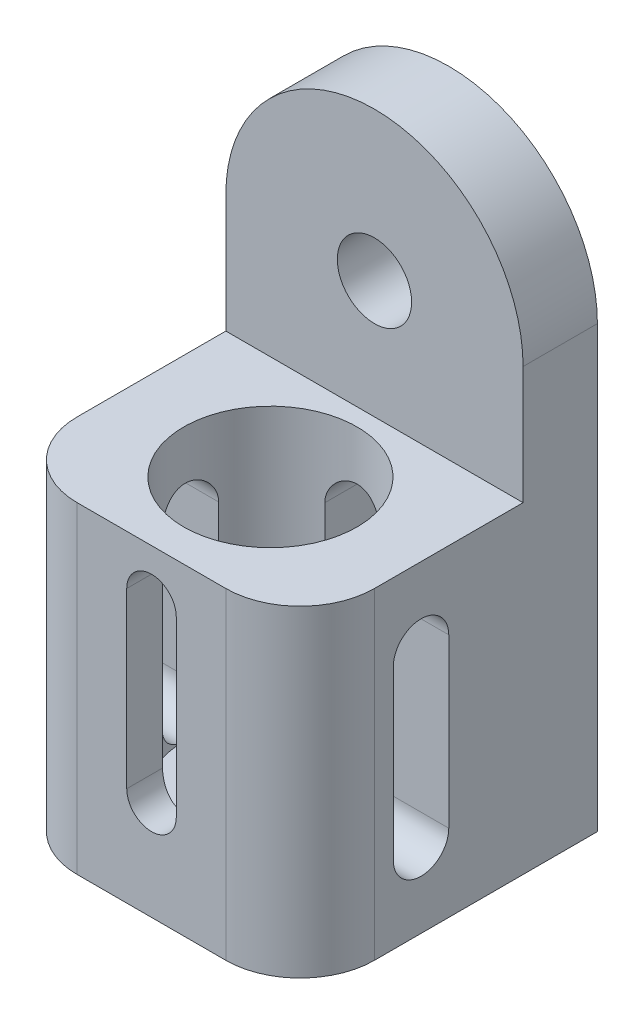
SolidWorks part; units mm, degrees
material "6061-T6 (SS)"
ref_plane "Front Plane" through (0, 0, 0) normal (0, 0, 1) x (1, 0, 0)
ref_plane "Top Plane" through (0, 0, 0) normal (0, 1, 0) x (1, 0, 0)
ref_plane "Right Plane" through (0, 0, 0) normal (1, 0, 0) x (0, 0, -1)
sketch "Sketch1" plane through (0, 0, 0) normal (0, 1, 0) x (1, 0, 0)
  line L1 (-38.1, -38.1) -> (38.1, -38.1)
  line L2 (-38.1, -38.1) -> (-38.1, 38.1)
  line L3 (-38.1, 38.1) -> (38.1, 38.1)
  line L4 (38.1, -38.1) -> (38.1, 38.1)
  line L5 (-38.1, -38.1) -> (38.1, 38.1) construction
  line L6 (-38.1, 38.1) -> (38.1, -38.1) construction
  point P0 (0, 0)
  dimension "D1" = 76.2
  dimension "D2" = 76.2
extrude "Boss-Extrude1" add sketch "Sketch1" against normal blind 82.55
sketch "Sketch2" plane through (0, 0, 0) normal (0, 1, 0) x (1, 0, 0)
  line L0 (38.1, -38.1) -> (38.1, 38.1) construction
  line L1 (-38.1, 38.1) -> (38.1, 38.1)
  line L2 (-38.1, 38.1) -> (-38.1, 19.05)
  line L3 (-38.1, 19.05) -> (38.1, 19.05)
  line L4 (38.1, 38.1) -> (38.1, 19.05)
  dimension "D1" = 19.05
extrude "Boss-Extrude2" add sketch "Sketch2" along normal blind 30.226
sketch "Sketch3" plane through (0, 0, -38.1) normal (0, 0, -1) x (-1, 0, 0)
  line L1 (-38.1, 30.226) -> (38.1, 30.226) construction
  line L2 (-38.1, 30.226) -> (38.1, 30.226)
  arc A1 (38.1, 30.226) -> (-38.1, 30.226) centre (0, 30.226) ccw
extrude "Boss-Extrude3" add sketch "Sketch3" against normal blind 19.05
fillet "Fillet1" radius 19.05 2 edges at (-38.1, -41.275, 38.1) (38.1, -41.275, 38.1)
sketch "Sketch4" plane through (38.1, 0, 0) normal (1, 0, 0) x (0, 0, -1)
  line L0 (-7.112, -19.812) -> (-7.112, -62.738) construction
  line L1 (0, -19.812) -> (0, -62.738)
  line L2 (-14.224, -19.812) -> (-14.224, -62.738)
  line L4 (-38.1, -82.55) -> (-38.1, 0) construction
  line L5 (-19.05, -82.55) -> (38.1, -82.55) construction
  arc A0 (0, -19.812) -> (-14.224, -19.812) centre (-7.112, -19.812) ccw
  arc A1 (-14.224, -62.738) -> (0, -62.738) centre (-7.112, -62.738) ccw
  point P2 (-7.112, -41.275)
  dimension "D1" = 14.224
  dimension "D2" = 30.988
  dimension "D3" = 42.926
  dimension "D4" = 19.812
extrude "Cut-Extrude1" cut sketch "Sketch4" against normal through all
sketch "Sketch5" plane through (0, 0, 0) normal (0, 1, 0) x (1, 0, 0)
  line L1 (-19.05, -38.1) -> (19.05, -38.1) construction
  circle A0 centre (0, -7.62) radius 22.225
  dimension "D1" = 44.45
  dimension "D2" = 30.48
extrude "Cut-Extrude2" cut sketch "Sketch5" against normal blind 69.85
sketch "Sketch6" plane through (0, 0, -38.1) normal (0, 0, -1) x (-1, 0, 0)
  line L0 (0, -19.812) -> (0, -62.738) construction
  line L1 (7.112, -19.812) -> (7.112, -62.738)
  line L2 (-7.112, -19.812) -> (-7.112, -62.738)
  line L3 (-38.1, -82.55) -> (38.1, -82.55) construction
  arc A0 (7.112, -19.812) -> (-7.112, -19.812) centre (0, -19.812) ccw
  arc A1 (-7.112, -62.738) -> (7.112, -62.738) centre (0, -62.738) ccw
  point P2 (0, -41.275)
  dimension "D1" = 14.224
  dimension "D2" = 42.926
  dimension "D3" = 19.812
extrude "Cut-Extrude3" cut sketch "Sketch6" against normal blind 50.8 and the other way through all
sketch "Sketch7" plane through (0, 0, 38.1) normal (0, 0, 1) x (1, 0, 0)
  line L0 (0, -12.7) -> (0, -57.15) construction
  line L1 (6.35, -12.7) -> (6.35, -57.15)
  line L2 (-6.35, -12.7) -> (-6.35, -57.15)
  line L3 (-19.05, -82.55) -> (19.05, -82.55) construction
  arc A0 (6.35, -12.7) -> (-6.35, -12.7) centre (0, -12.7) ccw
  arc A1 (-6.35, -57.15) -> (6.35, -57.15) centre (0, -57.15) ccw
  point P2 (0, -34.925)
  point P8 (0, 0)
  point P10 (0, -41.1451)
  dimension "D1" = 12.7
  dimension "D2" = 44.45
  dimension "D3" = 25.4
extrude "Cut-Extrude4" cut sketch "Sketch7" against normal blind 25.4
hole_wizard "3/8 (0.75) Diameter Hole1" positions "Sketch8" profile "Sketch9" hole size "3/8" standard "ANSI Inch" end condition through all
sketch "Sketch8" plane through (0, 0, -19.05) normal (0, 0, 1) x (1, 0, 0)
  point P0 (0, 30.226)
sketch "Sketch9" plane through (0, 30.226, -19.05) normal (1, 0, 0) x (0, -1, 0)
  line L0 (0, 0) -> (0, 19.05)
  line L1 (0, 19.05) -> (9.525, 19.05)
  line L2 (9.525, 19.05) -> (9.525, 0)
  line L5 (9.525, 0) -> (0, 0)
  line L11 (0, -6.35) -> (0, 107.95) construction
  dimension "Thru Hole Dia." = 19.05
  dimension "Thru Hole Depth" = 19.05
